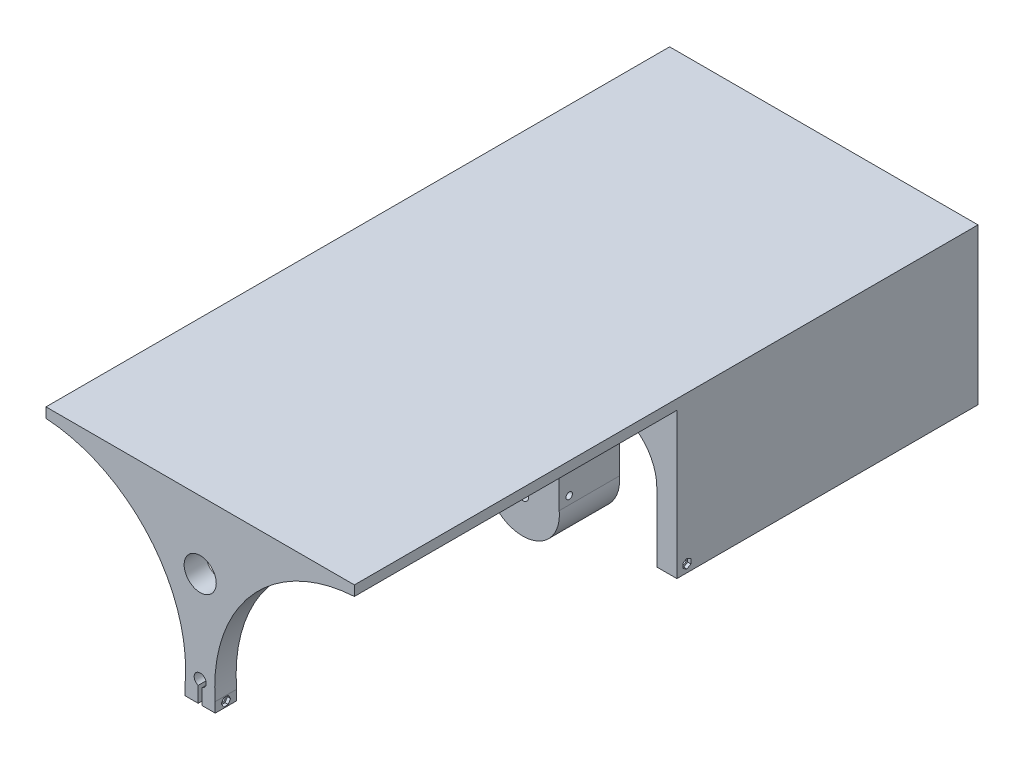
SolidWorks part; units mm, degrees
ref_plane "Płaszczyzna przednia" through (0, 0, 0) normal (0, 0, 1) x (1, 0, 0)
ref_plane "Płaszczyzna górna" through (0, 0, 0) normal (0, 1, 0) x (1, 0, 0)
ref_plane "Płaszczyzna prawa" through (0, 0, 0) normal (1, 0, 0) x (0, 0, -1)
sketch "Sketch1" plane through (0, 0, 0) normal (0, 0, 1) x (1, 0, 0)
  line L0 (-42.5, -47.31) -> (42.5, -47.31) construction
  line L1 (0, -47.31) -> (0, 0) construction
  line L2 (-42.5, -47.31) -> (42.5, -47.31) construction
  line L3 (-42.5, -13) -> (42.5, -13) construction
  line L4 (-42.5, -81.62) -> (42.5, -81.62) construction
  line L5 (-3.5724, -0.5005) -> (-51.9285, -14.3209)
  line L6 (3.5724, -0.5005) -> (51.9285, -14.3209)
  line L7 (-18.19, -47.31) -> (-18.19, -81.62)
  line L8 (-42.5, -47.31) -> (-66.81, -47.31) construction
  line L9 (-66.81, -47.31) -> (-66.81, -71.5216)
  line L10 (18.19, -47.31) -> (18.19, -81.62)
  line L12 (66.81, -47.31) -> (66.81, -71.5216)
  line L13 (0, 0) -> (-76.81, 0)
  line L14 (-76.81, 0) -> (-76.81, -47.31)
  line L15 (0, 0) -> (76.81, 0)
  line L16 (-18.19, -47.31) -> (-18.19, -4.6783) construction
  line L17 (18.19, -47.31) -> (18.19, -4.6783) construction
  line L18 (76.81, 0) -> (76.81, -47.31)
  line L19 (-76.81, -47.31) -> (-76.81, -81.62)
  line L20 (-76.81, -81.62) -> (-66.81, -81.62)
  line L21 (-66.81, -81.62) -> (-66.81, -71.5216)
  line L22 (66.81, -71.5216) -> (66.81, -81.62)
  line L23 (66.81, -81.62) -> (76.81, -81.62)
  line L24 (76.81, -81.62) -> (76.81, -47.31)
  circle A0 centre (-42.5, -47.31) radius 24.31
  circle A1 centre (42.5, -47.31) radius 24.31
  circle A4 centre (0, -13) radius 3
  arc A7 (-42.5, -13) -> (-42.5, -81.62) centre (-42.5, -47.31) ccw construction
  arc A8 (42.5, -81.62) -> (42.5, -13) centre (42.5, -47.31) ccw construction
  circle A9 centre (0, -13) radius 13 construction
  circle A10 centre (0, -83.41) radius 3
  circle A11 centre (0, -37.71) radius 8
  arc A12 (-18.19, -81.62) -> (18.19, -81.62) centre (0, -83.41) ccw
  point P9 (0, -47.31)
  point P34 (-76.81, -47.31)
  dimension "D1" = 48.62
  dimension "D2" = 48.62
  dimension "D3" = 42.5
  dimension "D4" = 10
  dimension "6" = 6
  dimension "D5" = 10
  dimension "D6" = 6
  dimension "D7" = 36.1
  dimension "D10" = 16
  dimension "D11" = 9.6
  dimension "D8" = 85
extrude "Boss-Extrude1" add sketch "Sketch1" against normal blind 30
sketch "Sketch2" plane through (0, 0, 0) normal (0, 0, 1) x (1, 0, 0)
  circle A0 centre (42.5, -47.31) radius 24.31
sketch "Sketch3" plane through (0, 0, -30) normal (0, 0, -1) x (-1, 0, 0)
  line L0 (0, 38.22) -> (0, -81.62) construction
  line L1 (-76.9535, -47.31) -> (-76.81, -81.62)
  line L2 (-16.5, -21.7) -> (16.5, -21.7) construction
  line L3 (16.5, -21.7) -> (16.5, -71.7) construction
  line L4 (16.5, -71.7) -> (-16.5, -71.7) construction
  line L5 (-16.5, -71.7) -> (-16.5, -21.7) construction
  line L6 (24.5, -12.8565) -> (24.5, -30.9706) construction
  line L7 (-42.5, -47.31) -> (42.5, -47.31) construction
  line L8 (-42.5, -12.8565) -> (42.5, -12.8565)
  line L9 (-42.5, -81.7635) -> (42.5, -81.7635)
  line L10 (-24.5, -12.8565) -> (-24.5, -30.9706) construction
  line L11 (-18.19, -47.31) -> (-18.19, 0)
  line L12 (-24.5, -12.8565) -> (-24.5, 0) construction
  line L13 (-24.5, 0) -> (24.5, 0)
  line L14 (24.5, 0) -> (24.5, -12.8565) construction
  line L15 (-24.5, 0) -> (-76.9535, 0)
  line L16 (-76.9535, 0) -> (-76.9535, -47.31)
  line L17 (0, 0) -> (76.9535, 0)
  line L18 (76.9535, 0) -> (76.9535, -47.31)
  line L19 (18.19, -47.31) -> (18.19, 0)
  line L20 (-66.81, -47.31) -> (-66.81, -71.7244)
  line L21 (66.81, -47.31) -> (66.81, -71.7244)
  line L22 (18.19, -19.7) -> (-18.19, -19.7)
  line L23 (-76.81, -81.62) -> (-66.81, -81.62)
  line L24 (-66.81, -81.62) -> (-66.81, -71.7244)
  line L25 (66.81, -71.7244) -> (66.81, -81.62)
  line L26 (66.81, -81.62) -> (76.81, -81.62)
  line L27 (76.81, -81.62) -> (76.9535, -47.31)
  circle A2 centre (-42.5, -47.31) radius 24.31
  circle A3 centre (42.5, -47.31) radius 24.31
  arc A4 (-42.5, -12.8565) -> (-42.5, -81.7635) centre (-42.5, -47.31) ccw
  arc A5 (42.5, -81.7635) -> (42.5, -12.8565) centre (42.5, -47.31) ccw
  point P7 (0, -21.7)
  point P18 (0, -47.31)
  point P35 (0, 0)
  point P50 (0, 0)
  dimension "D3" = 19.7
  dimension "D4" = 48.62
  dimension "D5" = 48.62
  dimension "D6" = 34.4535
  dimension "D10" = 34.4535
  dimension "D1" = 33
  dimension "D2" = 50
  dimension "D7" = 18
  dimension "D8" = 2
  dimension "D9" = 119.84
extrude "Boss-Extrude2" add sketch "Sketch3" along normal blind 120
sketch "Sketch5" plane through (0, 0, 0) normal (0, 0, 1) x (1, 0, 0)
  line L1 (-76.81, 0) -> (-76.81, -9)
  line L2 (-76.81, -9) -> (76.81, -9)
  line L3 (76.81, 0) -> (76.81, -81.62) construction
  line L4 (76.81, -9) -> (76.81, 0)
  line L5 (76.81, 0) -> (-76.81, 0) construction
  line L6 (76.81, 0) -> (-76.81, 0)
  line L7 (-76.81, 0) -> (-76.81, 6)
  line L8 (-76.81, 6) -> (76.81, 6)
  line L9 (76.81, 6) -> (76.81, 0)
  line M9 (76.81, -81.62) -> (76.81, 0)
  line M10 (76.81, 0) -> (-76.81, 0)
  line M11 (-76.81, 0) -> (-76.81, -81.62)
  dimension "D1" = 153.62
  dimension "D2" = 9
  dimension "D3" = 6
extrude "Boss-Extrude3" add sketch "Sketch5" along normal blind 150 contours L2 M11 M9 M10 | L9 L8 L7 M10
sketch "Sketch6" plane through (0, 0, 0) normal (0, 0, -1) x (-1, 0, 0)
  line L1 (-76.81, 6) -> (76.81, 6)
  line L2 (-76.81, 6) -> (-76.81, 0)
  line L3 (-76.81, 0) -> (76.81, 0)
  line L4 (76.81, 6) -> (76.81, 0)
  line L5 (-76.81, 6) -> (76.81, 0) construction
  line L6 (-76.81, 0) -> (76.81, 6) construction
  point P4 (0, 3)
extrude "Boss-Extrude4" add sketch "Sketch6" along normal up to surface (150 mm away) up to face at (0, -42.2083, -150)
sketch "Sketch7" plane through (0, 0, 150) normal (0, 0, 1) x (1, 0, 0)
  line L0 (-14.6943, -94.1316) -> (-76.81, -9) construction
  line L1 (14.6943, -94.1316) -> (76.81, -9) construction
  line L2 (-76.81, -9) -> (-76.81, 6)
  line L3 (-76.81, 6) -> (76.81, 6)
  line L4 (76.81, 6) -> (76.81, -9)
  line L5 (76.81, -9) -> (76.81, -81.62) construction
  line L6 (-7.5, -89) -> (-7.5, -94)
  line L7 (-7.5, -94) -> (7.5, -94)
  line L8 (0, -94) -> (0, -9) construction
  line L9 (-76.81, -9) -> (76.81, -9) construction
  line L10 (7.5, -89) -> (7.5, -94)
  line L11 (-76.81, -9) -> (76.81, -9) construction
  circle A0 centre (0, -83.41) radius 18.19 construction
  arc A1 (-76.81, -9) -> (-7.5, -89) centre (-81.2454, -82.867) cw
  arc A2 (76.81, -9) -> (7.5, -89) centre (81.2454, -82.867) ccw
  line M4 (-76.81, 6) -> (-76.81, -9)
  line M5 (-76.81, -9) -> (76.81, -9)
  line M6 (76.81, -9) -> (76.81, 6)
  line M7 (76.81, 6) -> (-76.81, 6)
  dimension "D1" = 36.38
  dimension "D3" = 74
  dimension "D2" = 15
  dimension "D4" = 5
  dimension "D5" = 85
extrude "Boss-Extrude5" add sketch "Sketch7" along normal blind 10.65 contours A0 L1 L0 M5 | M7 M4 M5 M6 | A0
sketch "Sketch8" plane through (0, 0, 160.65) normal (0, 0, 1) x (1, 0, 0)
  circle A0 centre (0, -83.41) radius 3 construction
  circle A1 centre (0, -83.41) radius 3 construction
  circle A2 centre (0, -37.71) radius 8 construction
  circle A3 centre (0, -37.71) radius 8 construction
  circle A4 centre (0, -83.41) radius 3
  circle A5 centre (0, -37.71) radius 8
  dimension "D1" = 6
  dimension "D2" = 16
extrude "Cut-Extrude1" cut sketch "Sketch8" against normal up to next
sketch "Sketch9" plane through (0, 0, -30) normal (0, 0, -1) x (-1, 0, 0)
  circle A0 centre (0, -37.71) radius 13.5
  circle A1 centre (0, -37.71) radius 8 construction
  dimension "D1" = 27
extrude "Cut-Extrude2" cut sketch "Sketch9" against normal blind 22
sketch "Sketch10" plane through (0, -19.7, 0) normal (0, -1, 0) x (1, 0, 0)
  line L0 (-18.19, -150) -> (18.19, -150) construction
  line L1 (8, -102.85) -> (18.19, -102.85) construction
  line L2 (18.19, -150) -> (18.19, -30) construction
  line L3 (-8, -102.85) -> (-18.19, -102.85) construction
  line L4 (-18.19, -150) -> (-18.19, -30) construction
  circle A0 centre (-6, -102.85) radius 2
  circle A1 centre (6, -102.85) radius 2
  dimension "D1" = 4
  dimension "D3" = 47.15
  dimension "D4" = 12
  dimension "D2" = 47.15
extrude "Cut-Extrude3" cut sketch "Sketch10" against normal blind 6.7
sketch "Sketch11" plane through (0, 0, 160.65) normal (0, 0, 1) x (1, 0, 0)
  line L0 (-76.81, 6) -> (-76.81, -4)
  line L1 (-76.81, 6) -> (-76.81, -9) construction
  line L2 (-76.81, -4) -> (76.81, -4)
  line L3 (76.81, -9) -> (76.81, 6) construction
  line L4 (76.81, -4) -> (76.81, 6)
  line L5 (76.81, 6) -> (-76.81, 6) construction
  line L6 (76.81, 6) -> (-76.81, 6)
  dimension "D1" = 10
sketch "Sketch12" plane through (0, 0, -150) normal (0, 0, -1) x (-1, 0, 0)
  line L0 (-20.342, -37.31) -> (20.342, -37.31)
  line L1 (20.342, -37.31) -> (20.342, -47.31)
  line L2 (20.342, -47.31) -> (-20.342, -47.31)
  line L3 (-20.342, -47.31) -> (-20.342, -37.31)
  arc A0 (-18.19, -47.31) -> (-66.81, -47.31) centre (-42.5, -47.31) ccw construction
  arc A1 (66.81, -47.31) -> (18.19, -47.31) centre (42.5, -47.31) ccw construction
  dimension "D1" = 10
extrude "Cut-Extrude5" cut sketch "Sketch12" against normal up to surface (120 mm away) up to face at (-13.5, -37.71, -30)
sketch "Sketch13" plane through (0, 0, -150) normal (0, 0, -1) x (-1, 0, 0)
  line L0 (-15.342, -37.31) -> (-20.342, -37.31) construction
  line L1 (-20.342, -37.31) -> (-20.342, -47.31)
  line L2 (-20.342, -47.31) -> (-66.81, -47.31)
  line L3 (-66.81, -81.62) -> (-66.81, -47.31) construction
  line L4 (-66.81, -47.31) -> (-66.81, -81.62)
  line L5 (-76.81, -81.62) -> (-66.81, -81.62) construction
  line L6 (-66.81, -81.62) -> (-15.342, -81.62)
  line L7 (-15.342, -81.62) -> (-15.342, -37.31)
  line L8 (-15.342, -37.31) -> (-15.342, -19.7)
  line L9 (18.19, -19.7) -> (-18.19, -19.7) construction
  line L10 (-42.5, -47.31) -> (-42.5, -81.6495) construction
  line L11 (-47.5, -81.62) -> (-47.5, -47.31)
  line L12 (-47.5, -47.31) -> (-37.5, -47.31)
  line L13 (-37.5, -47.31) -> (-37.5, -81.62)
  line L14 (-37.5, -81.62) -> (-47.5, -81.62)
  line L15 (0, -19.7) -> (0, -101.6879) construction
  circle A0 centre (-42.5, -47.31) radius 24.31
  arc A1 (-20.342, -37.31) -> (-66.81, -47.31) centre (-42.5, -47.31) ccw construction
  arc A2 (-18.19, -81.62) -> (18.19, -81.62) centre (0, -83.41) ccw construction
  line M16 (-66.81, -81.62) -> (-66.81, -47.31)
  line M18 (-20.342, -37.31) -> (-18.19, -37.31)
  line M19 (-18.19, -37.31) -> (-18.19, -19.7)
  line M20 (-18.19, -19.7) -> (18.19, -19.7)
  dimension "D1" = 5
  dimension "D2" = 10
  dimension "D3" = 5
extrude "Boss-Extrude6" add sketch "Sketch13" against normal blind 10 contours A0 L13 L6 L7 L8 M20 M19 M18 | A0 L6 L11 M16
extrude "Cut-Extrude4" cut sketch "Sketch11" against normal through all
ref_plane "Plane1" through (0, 0, 0) normal (1, 0, 0) x (0, 0, -1)
mirror "Mirror1" about plane through (0, 0, 0) normal (1, 0, 0) of "Boss-Extrude6"
sketch "Sketch14" plane through (0, -94, 0) normal (0, -1, 0) x (1, 0, 0)
  line L0 (-1, 160.65) -> (-1, 150)
  line L1 (-7.5, 160.65) -> (7.5, 160.65) construction
  line L2 (-76.81, 150) -> (76.81, 150) construction
  line L3 (-1, 150) -> (1, 150)
  line L4 (1, 150) -> (1, 160.65)
  line L5 (1, 160.65) -> (-1, 160.65)
  line L6 (0, -42.691) -> (0, 42.691) construction
  dimension "D1" = 2
  dimension "D2" = 1
extrude "Cut-Extrude6" cut sketch "Sketch14" against normal up to next
sketch "Sketch17" plane through (-7.5, 0, 0) normal (-1, 0, 0) x (0, 0, 1)
  line L1 (150, -89) -> (160.65, -89)
  line L2 (150, -89) -> (150, -94)
  line L3 (150, -94) -> (160.65, -94)
  line L4 (160.65, -89) -> (160.65, -94)
  line L5 (150, -89) -> (160.65, -94) construction
  line L6 (150, -94) -> (160.65, -89) construction
  point P4 (155.325, -91.5)
hole_wizard "CSK for M2 Countersunk Flat Head Screw1" positions "Sketch17" profile "Sketch18" countersink size "M2" standard "DIN"
sketch "Sketch18" plane through (-7.5, -91.5, 155.325) normal (0, 1, 0) x (0, 0, 1)
  line L0 (0, 0) -> (0, 17.221)
  line L1 (0, 17.221) -> (1.2, 16.5)
  line L2 (1.2, 16.5) -> (1.2, 1)
  line L3 (1.2, 1) -> (2.2, 0)
  line L5 (2.2, 0) -> (0, 0)
  line L6 (-1.2, 1) -> (-2.2, 0) construction
  line L10 (0, 17.221) -> (-1.2, 16.5) construction
  line L11 (0, -6.35) -> (0, 107.95) construction
  dimension "Hole Dia." = 2.4
  dimension "Hole Depth" = 16.5
  dimension "Near C'Sink Dia." = 4.4
  dimension "Near C'Sink Angle" = 90
  dimension "Drill Angle" = 118
sketch "Sketch19" plane through (7.5, 0, 0) normal (1, 0, 0) x (0, 0, -1)
  line L0 (-160.65, -89) -> (-150, -89) construction
  line L1 (-154.1703, -93.5) -> (-153.0156, -91.5)
  line L2 (-153.0156, -91.5) -> (-154.1703, -89.5)
  line L3 (-154.1703, -89.5) -> (-156.4797, -89.5)
  line L4 (-156.4797, -89.5) -> (-157.6344, -91.5)
  line L5 (-157.6344, -91.5) -> (-156.4797, -93.5)
  line L6 (-156.4797, -93.5) -> (-154.1703, -93.5)
  circle A0 centre (-155.325, -91.5) radius 2 construction
  dimension "D1" = 4
extrude "Cut-Extrude7" cut sketch "Sketch19" against normal blind 1.6
sketch "Sketch22" plane through (-18.19, 0, 0) normal (-1, 0, 0) x (0, 0, 1)
  line L0 (0, -77.65) -> (0, -81.62) construction
  line L1 (0, -47.31) -> (0, -81.62) construction
  line L2 (0, -81.62) -> (-5, -81.62) construction
  line L3 (-30, -81.62) -> (0, -81.62) construction
  line L4 (-5, -81.62) -> (-5, -77.65) construction
  line L5 (-5, -77.65) -> (0, -77.65) construction
  circle A0 centre (-5, -77.65) radius 1.6
  dimension "D3" = 3.2
  dimension "D1" = 3.97
  dimension "D2" = 5
extrude "Cut-Extrude8" cut sketch "Sketch22" against normal blind 4
ref_plane "Plane2" through (0, 0, 0) normal (-1, 0, 0) x (0, 0, 1)
mirror "Mirror2" about plane through (0, 0, 0) normal (1, 0, 0) of "Cut-Extrude8"
sketch "Sketch23" plane through (-76.81, 0, 0) normal (-1, 0, 0) x (0, 0, 1)
  line L0 (0, -9) -> (0, -81.62) construction
  line L1 (-5, -75.3406) -> (-7, -76.4953)
  line L2 (-7, -76.4953) -> (-7, -78.8047)
  line L3 (-7, -78.8047) -> (-5, -79.9594)
  line L4 (-5, -79.9594) -> (-3, -78.8047)
  line L5 (-3, -78.8047) -> (-3, -76.4953)
  line L6 (-3, -76.4953) -> (-5, -75.3406)
  circle A0 centre (-5, -77.65) radius 1.6 construction
  circle A1 centre (-5, -77.65) radius 1.6 construction
  circle A2 centre (-5, -77.65) radius 2 construction
  dimension "D1" = 4
extrude "Cut-Extrude9" cut sketch "Sketch23" against normal blind 1.6
mirror "Mirror3" about plane through (0, 0, 0) normal (1, 0, 0) of "Cut-Extrude9"
sketch "Sketch24" plane through (-66.81, 0, 0) normal (1, 0, 0) x (0, 0, -1)
  circle A0 centre (5, -77.65) radius 1.6 construction
  circle A1 centre (5, -77.65) radius 1.6 construction
  circle A2 centre (5, -77.65) radius 1.2
  dimension "D1" = 2.4
extrude "Cut-Extrude10" cut sketch "Sketch24" against normal up to next
mirror "Mirror4" about plane through (0, 0, 0) normal (1, 0, 0) of "Cut-Extrude10"
